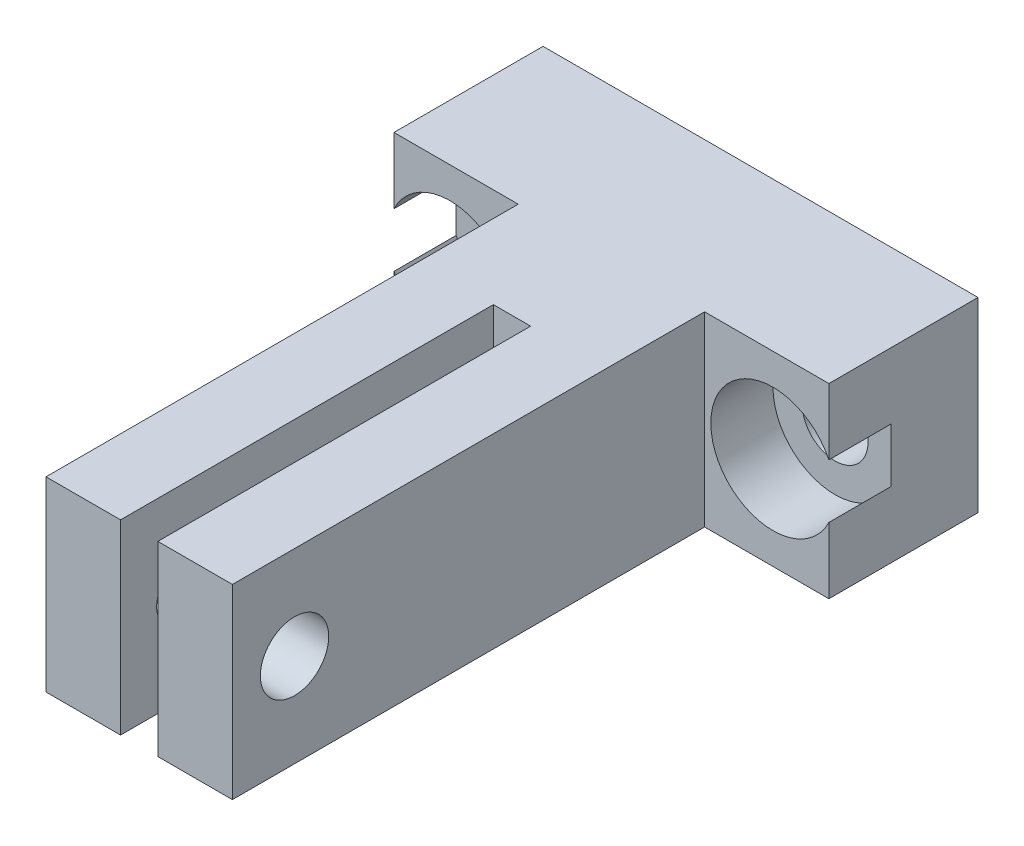
SolidWorks part; units mm, degrees
ref_plane "Front Plane" through (0, 0, 0) normal (0, 0, 1) x (1, 0, 0)
ref_plane "Top Plane" through (0, 0, 0) normal (0, 1, 0) x (1, 0, 0)
ref_plane "Right Plane" through (0, 0, 0) normal (1, 0, 0) x (0, 0, -1)
sketch "草图1" plane through (0, 0, 0) normal (0, 0, 1) x (1, 0, 0)
  line L1 (-193.5, -27) -> (-178.5, -27)
  line L2 (-193.5, -27) -> (-193.5, -12)
  line L3 (-193.5, -12) -> (-178.5, -12)
  line L4 (-178.5, -27) -> (-178.5, -12)
  dimension "D1" = 15
  dimension "D2" = 15
extrude "凸台-拉伸1" add sketch "草图1" along normal blind 50
sketch "草图2" plane through (0, 0, 50) normal (0, 0, 1) x (1, 0, 0)
  line L0 (-178.5, -12) -> (-193.5, -12) construction
  line L1 (-187.5, -12) -> (-184.5, -12)
  line L2 (-187.5, -12) -> (-187.5, -27)
  line L3 (-187.5, -27) -> (-184.5, -27)
  line L4 (-184.5, -12) -> (-184.5, -27)
  line L5 (-193.5, -27) -> (-178.5, -27) construction
  line L6 (-193.5, -12) -> (-193.5, -27) construction
  dimension "D1" = 3
  dimension "D2" = 6
extrude "切除-拉伸1" cut sketch "草图2" against normal blind 30
sketch "草图3" plane through (0, 0, 0) normal (0, 0, -1) x (-1, 0, 0)
  line L0 (186, -27) -> (186, -10.7276) construction
  line L1 (178.5, -27) -> (168.5, -27)
  line L2 (178.5, -27) -> (178.5, -12)
  line L3 (178.5, -12) -> (168.5, -12)
  line L4 (168.5, -27) -> (168.5, -12)
  line L5 (193.5, -27) -> (178.5, -27) construction
  line L6 (203.5, -27) -> (203.5, -12)
  line L7 (193.5, -12) -> (203.5, -12)
  line L8 (193.5, -27) -> (193.5, -12)
  line L9 (193.5, -27) -> (203.5, -27)
  dimension "D1" = 15
  dimension "D2" = 10
extrude "凸台-拉伸2" add sketch "草图3" against normal blind 12
hole_wizard "M5 凹头盖螺钉的柱形沉头孔2" positions "草图5" profile "草图4" counterbore size "M5" standard "Ansi Metric" end condition through all
sketch "草图5" plane through (0, 0, 12) normal (0, 0, 1) x (1, 0, 0)
  line L0 (-203.5, -27) -> (-203.5, -12) construction
  line L1 (-168.5, -12) -> (-168.5, -27) construction
  point P0 (-199, -19.5)
  point P2 (-173, -19.5)
  dimension "D1" = 4.5
  dimension "D2" = 4.5
sketch "草图4" plane through (-199, -19.5, 12) normal (1, 0, 0) x (0, -1, 0)
  line L0 (0, 0) -> (0, 12)
  line L1 (0, 12) -> (2.65, 12)
  line L3 (2.65, 12) -> (2.65, 5)
  line L4 (2.65, 5) -> (5, 5)
  line L5 (5, 5) -> (5, 0)
  line L7 (5, 0) -> (0, 0)
  line L11 (0, -6.35) -> (0, 107.95) construction
  dimension "通孔孔直径" = 5.3
  dimension "通孔孔深度" = 12
  dimension "柱形沉头孔直径" = 10
  dimension "柱形沉头孔深度" = 5
sketch "草图8" plane through (-178.5, 0, 0) normal (1, 0, 0) x (0, 0, -1)
  line L0 (-50, -27) -> (-50, -12) construction
  circle A0 centre (-45, -19.5) radius 2.75
  dimension "D1" = 5.5
  dimension "D2" = 5
extrude "切除-拉伸2" cut sketch "草图8" against normal up to next
hole_wizard "M5x0.8 螺纹孔1" positions "草图10" profile "草图9" tap size "M5x0.8" standard "Ansi Metric" end condition through all
sketch "草图10" plane through (-187.5, 0, 0) normal (1, 0, 0) x (0, 0, -1)
  point P0 (-45, -19.5)
sketch "草图9" plane through (-187.5, -19.5, 45) normal (0, 1, 0) x (0, 0, -1)
  line L0 (0, 0) -> (0, 16)
  line L1 (0, 16) -> (2.1, 16)
  line L2 (2.1, 16) -> (2.1, 0)
  line L5 (2.1, 0) -> (0, 0)
  line L11 (0, -6.35) -> (0, 107.95) construction
  dimension "通孔螺纹孔钻头直径" = 4.2
  dimension "通孔螺纹孔钻头深度" = 16
cosmetic thread "孔螺蚊线1" parameters "D2"=5
